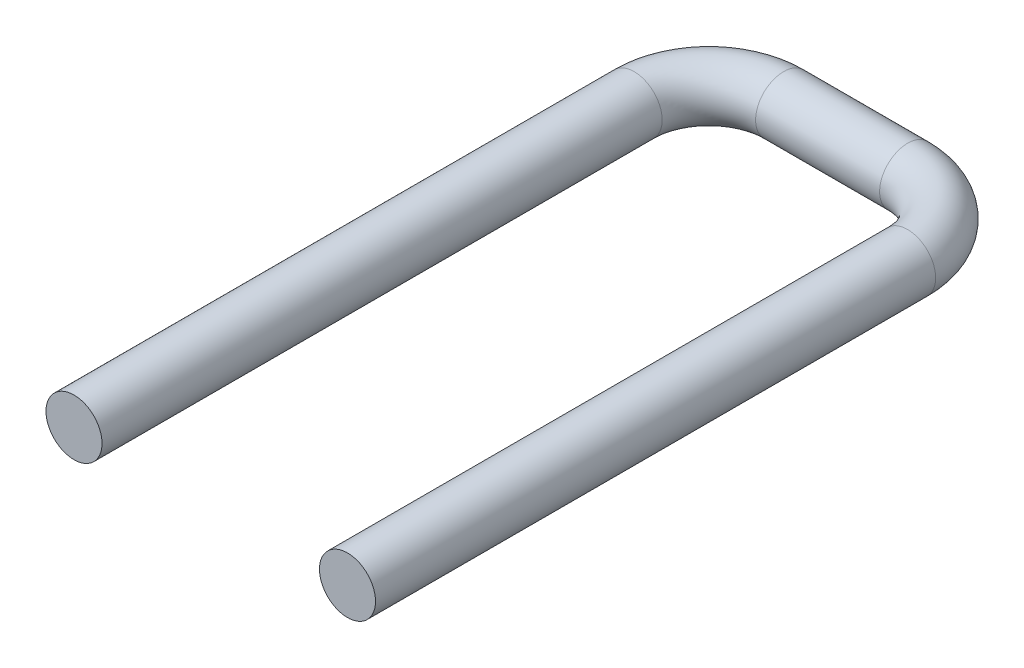
SolidWorks part; units mm, degrees
ref_plane "Спереди" through (0, 0, 0) normal (0, 0, 1) x (1, 0, 0)
ref_plane "Сверху" through (0, 0, 0) normal (0, 1, 0) x (1, 0, 0)
ref_plane "Справа" through (0, 0, 0) normal (1, 0, 0) x (0, 0, -1)
sketch "Эскиз1" plane through (0, 0, 0) normal (0, 1, 0) x (1, 0, 0)
  line L1 (-2.9217, 0.3267) -> (-2.9217, 15.3197)
  line L2 (-0.9217, 17.3197) -> (2.3983, 17.3197)
  line L8 (4.3983, 15.3197) -> (4.3983, 0.3267)
  arc A0 (-0.9217, 17.3197) -> (-2.9217, 15.3197) centre (-0.9217, 15.3197) ccw
  arc A1 (4.3983, 15.3197) -> (2.3983, 17.3197) centre (2.3983, 15.3197) ccw
  point P14 (-2.9217, 17.3197)
  point P18 (4.3983, 17.3197)
  dimension "D1" = 2
  dimension "D2" = 7.32
ref_plane "Плоскость2" through (-2.9217, 0, -0.3267) normal (0, 0, -1) x (-1, 0, 0)
sketch "Эскиз7" plane through (-2.9217, 0, -0.3267) normal (0, 0, -1) x (-1, 0, 0)
  circle A0 centre (0, 0) radius 0.75
sweep "По траектории9" add profiles "Эскиз7" path "Эскиз1"
